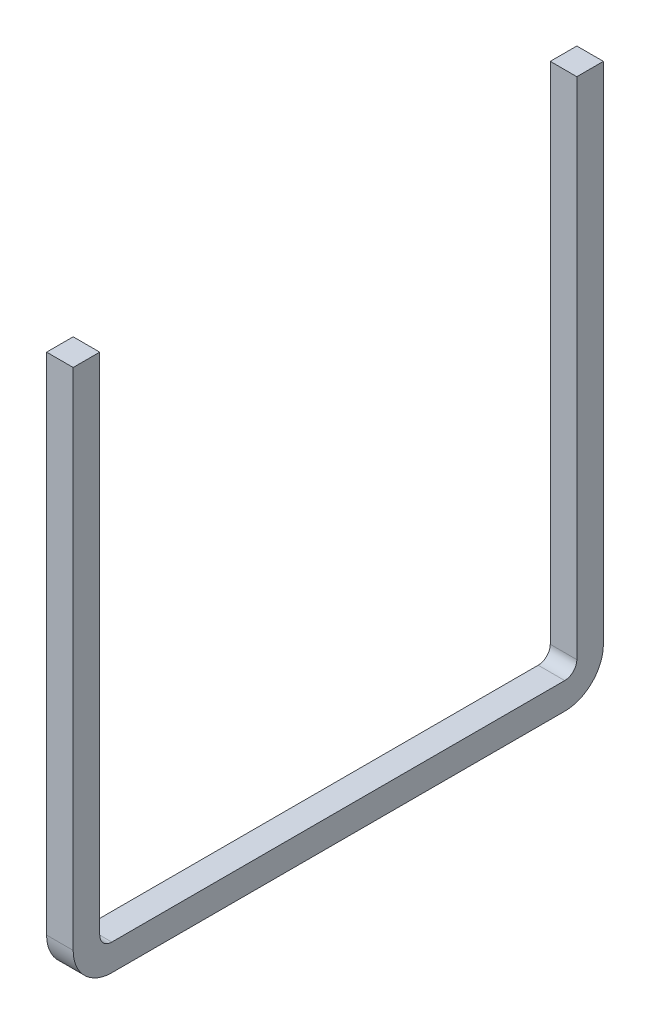
SolidWorks part; units mm, degrees
material "Acrylic (Medium-high impact)"
ref_plane "Front Plane" through (0, 0, 0) normal (0, 0, 1) x (1, 0, 0)
ref_plane "Top Plane" through (0, 0, 0) normal (0, 1, 0) x (1, 0, 0)
ref_plane "Right Plane" through (0, 0, 0) normal (1, 0, 0) x (0, 0, -1)
sketch "Sketch1" plane through (0, 0, 0) normal (1, 0, 0) x (0, 0, -1)
  line L0 (-47.625, 0) -> (47.625, 0)
  line L1 (55.753, 8.128) -> (55.753, 114.3)
  line L2 (55.753, 114.3) -> (50.165, 114.3)
  line L3 (50.165, 114.3) -> (50.165, 8.128)
  line L4 (47.625, 5.588) -> (-47.625, 5.588)
  line L5 (-50.165, 8.128) -> (-50.165, 114.3)
  line L6 (-50.165, 114.3) -> (-55.753, 114.3)
  line L7 (-55.753, 114.3) -> (-55.753, 8.128)
  arc A0 (-50.165, 8.128) -> (-47.625, 5.588) centre (-47.625, 8.128) ccw
  arc A1 (47.625, 5.588) -> (50.165, 8.128) centre (47.625, 8.128) ccw
  arc A2 (-55.753, 8.128) -> (-47.625, 0) centre (-47.625, 8.128) ccw
  arc A3 (47.625, 0) -> (55.753, 8.128) centre (47.625, 8.128) ccw
  point P12 (55.753, 0)
  dimension "D4" = 2.54
  dimension "D5" = 114.3
  dimension "D1" = 5.588
  dimension "D2" = 5.588
  dimension "D3" = 100.33
extrude "Boss-Extrude1" add sketch "Sketch1" along normal blind 5.588
sketch "Sketch2" [suppressed] plane through (5.588, 0, 0) normal (1, 0, 0) x (0, 0, -1)
  line L0 (-57.912, 114.3) -> (-51.562, 114.3)
  line L1 (-51.562, 114.3) -> (-51.562, 14.478)
  line L2 (-49.022, 11.938) -> (49.022, 11.938)
  line L3 (51.562, 14.478) -> (51.562, 114.3)
  line L4 (51.562, 114.3) -> (57.912, 114.3)
  line L5 (55.372, 5.588) -> (-55.372, 5.588) construction
  line L6 (-57.912, 8.128) -> (-57.912, 114.3) construction
  line L7 (57.912, 114.3) -> (57.912, 8.128) construction
  line L8 (-57.912, 8.128) -> (-57.912, 114.3)
  line L9 (55.372, 5.588) -> (-55.372, 5.588)
  line L10 (57.912, 114.3) -> (57.912, 8.128)
  arc A1 (-51.562, 14.478) -> (-49.022, 11.938) centre (-49.022, 14.478) ccw
  arc A2 (49.022, 11.938) -> (51.562, 14.478) centre (49.022, 14.478) ccw
  arc A3 (-57.912, 8.128) -> (-55.372, 5.588) centre (-55.372, 8.128) ccw construction
  arc A4 (55.372, 5.588) -> (57.912, 8.128) centre (55.372, 8.128) ccw construction
  arc A5 (-57.912, 8.128) -> (-55.372, 5.588) centre (-55.372, 8.128) ccw
  arc A6 (55.372, 5.588) -> (57.912, 8.128) centre (55.372, 8.128) ccw
  dimension "D3" = 2.54
  dimension "D1" = 6.35
  dimension "D2" = 6.35
extrude "Boss-Extrude2" [suppressed] add sketch "Sketch2" against normal up to surface (5.588 mm away)
